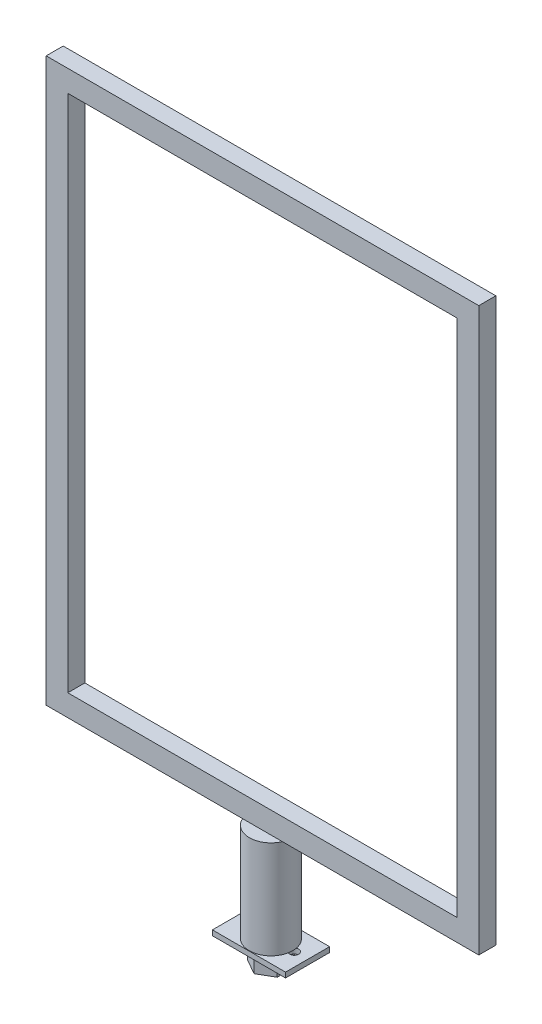
SolidWorks part; units mm, degrees
ref_plane "Front Plane" through (0, 0, 0) normal (0, 0, 1) x (1, 0, 0)
ref_plane "Top Plane" through (0, 0, 0) normal (0, 1, 0) x (1, 0, 0)
ref_plane "Right Plane" through (0, 0, 0) normal (1, 0, 0) x (0, 0, -1)
sketch "Sketch1" plane through (0, 0, 0) normal (0, 1, 0) x (1, 0, 0)
  line L1 (0, 10) -> (-8.6603, 5)
  line L2 (-8.6603, 5) -> (-8.6603, -5)
  line L3 (-8.6603, -5) -> (0, -10)
  line L4 (0, -10) -> (8.6603, -5)
  line L5 (8.6603, -5) -> (8.6603, 5)
  line L6 (8.6603, 5) -> (0, 10)
  circle A0 centre (0, 0) radius 8.6603 construction
  dimension "D1" = 10
extrude "Boss-Extrude1" add sketch "Sketch1" along normal blind 10 contours L1 L2 L3 L4 L5 L6
sketch "Sketch2" plane through (0, 10, 0) normal (0, 1, 0) x (1, 0, 0)
  line L0 (0, 0) -> (0, 6.3089) construction
  line L1 (-21.4725, -12.9315) -> (21.4725, -12.9315)
  line L2 (-21.4725, -12.9315) -> (-21.4725, 12.9315)
  line L3 (-21.4725, 12.9315) -> (21.4725, 12.9315)
  line L4 (21.4725, -12.9315) -> (21.4725, 12.9315)
  line L5 (-21.4725, -12.9315) -> (21.4725, 12.9315) construction
  line L6 (-21.4725, 12.9315) -> (21.4725, -12.9315) construction
  line L7 (-8.6603, 5) -> (-8.6603, -5) construction
  circle A0 centre (-13.6603, 0) radius 2.6
  circle A1 centre (13.6603, 0) radius 2.6
  point P0 (0, 0)
  dimension "D2" = 5.2
  dimension "D1" = 5
extrude "Boss-Extrude2" add sketch "Sketch2" along normal blind 3
sketch "Sketch3" plane through (0, 13, 0) normal (0, 1, 0) x (1, 0, 0)
  circle A0 centre (0, 0) radius 12.7
  dimension "D1" = 25.4
extrude "Boss-Extrude5" add sketch "Sketch3" along normal blind 57.4765 contours A0
sketch "Sketch4" plane through (0, 0, 0) normal (0, 0, 1) x (1, 0, 0)
  line L0 (12.7, 70.4765) -> (-12.7, 70.4765) construction
  line L1 (-114.3, 83.1765) -> (114.3, 83.1765)
  line L2 (-114.3, 83.1765) -> (-114.3, 387.9765)
  line L3 (-114.3, 387.9765) -> (114.3, 387.9765)
  line L4 (114.3, 83.1765) -> (114.3, 387.9765)
  line L5 (-114.3, 83.1765) -> (114.3, 387.9765) construction
  line L6 (-114.3, 387.9765) -> (114.3, 83.1765) construction
  line L8 (-127, 70.4765) -> (127, 70.4765)
  line L9 (-127, 70.4765) -> (-127, 400.6765)
  line L10 (-127, 400.6765) -> (127, 400.6765)
  line L11 (127, 70.4765) -> (127, 400.6765)
  line L12 (-127, 70.4765) -> (127, 400.6765) construction
  line L13 (-127, 400.6765) -> (127, 70.4765) construction
  point P0 (0, 235.5765)
  point P9 (0, 235.5765)
  dimension "D1" = 304.8
  dimension "D2" = 228.6
  dimension "D3" = 12.7
  dimension "D4" = 12.7
extrude "Boss-Extrude4" add sketch "Sketch4" along normal blind 5 and the other way blind 5
sketch "Sketch5" plane through (0, 0, 5) normal (0, 0, 1) x (1, 0, 0)
  line L0 (-114.3, 387.9765) -> (114.3, 83.1765) construction
  line L1 (114.3, 387.9765) -> (-114.3, 387.9765) construction
  line L2 (114.3, 83.1765) -> (114.3, 387.9765) construction
  line L3 (-114.3, 83.1765) -> (114.3, 83.1765) construction
  point P8 (0, 235.5765)
